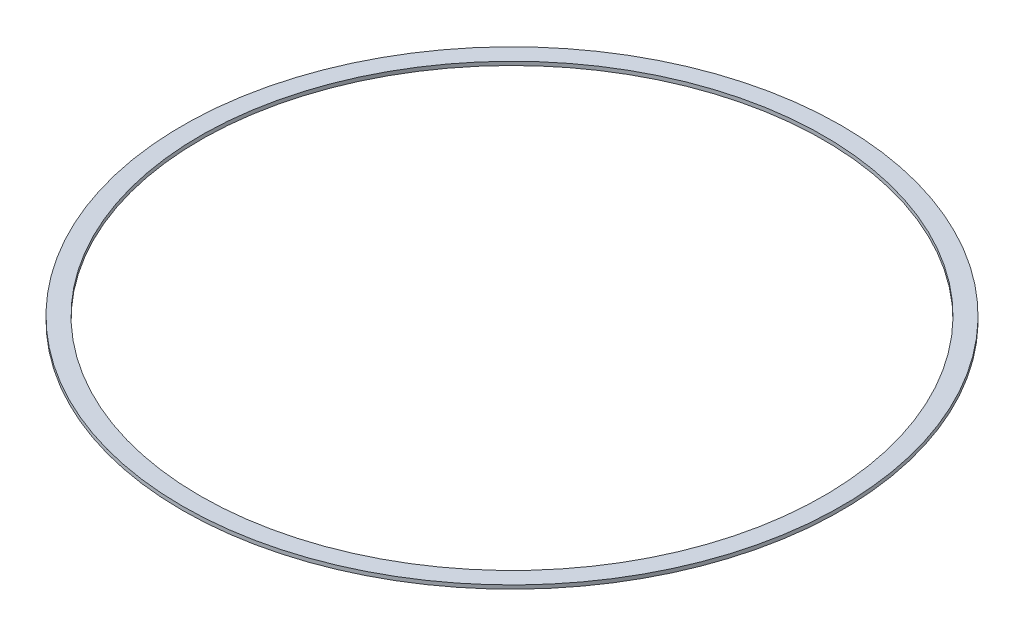
SolidWorks part; units mm, degrees
material "6061-T6 (SS)"
ref_plane "Front Plane" through (0, 0, 0) normal (0, 0, 1) x (1, 0, 0)
ref_plane "Top Plane" through (0, 0, 0) normal (0, 1, 0) x (1, 0, 0)
ref_plane "Right Plane" through (0, 0, 0) normal (1, 0, 0) x (0, 0, -1)
sketch "Sketch1" plane through (0, 0, 0) normal (0, 1, 0) x (1, 0, 0)
  circle A0 centre (0, 0) radius 214.6681
  circle A1 centre (0, 0) radius 226.8601
  dimension "D1" = 453.7202
  dimension "D2" = 429.3362
extrude "Boss-Extrude1" add sketch "Sketch1" along normal blind 2.54
ref_plane "Plane1" through (0, 1.27, 0) normal (0, 1, 0) x (1, 0, 0)
